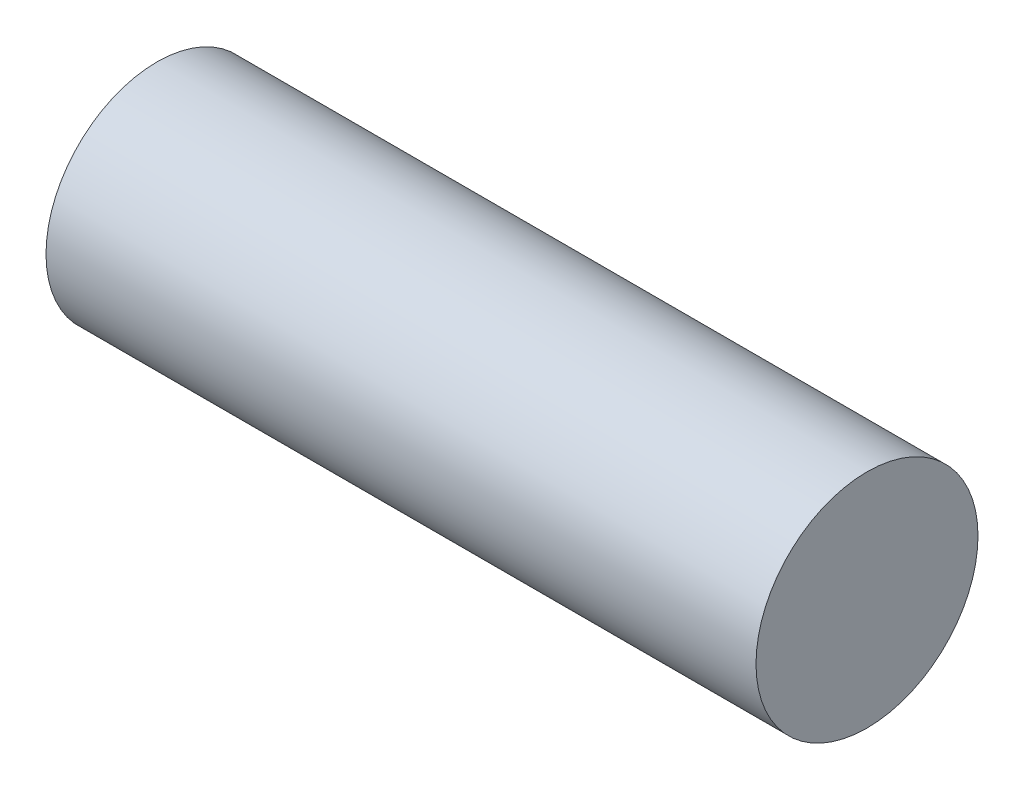
SolidWorks part; units mm, degrees
material "Chrome Stainless Steel"
ref_plane "Front Plane" through (0, 0, 0) normal (0, 0, 1) x (1, 0, 0)
ref_plane "Top Plane" through (0, 0, 0) normal (0, 1, 0) x (1, 0, 0)
ref_plane "Right Plane" through (0, 0, 0) normal (1, 0, 0) x (0, 0, -1)
sketch "Sketch2" plane through (0, 0, 0) normal (1, 0, 0) x (0, 0, -1)
  circle A0 centre (0, 0) radius 3
  dimension "D1" = 6
extrude "Boss-Extrude1" add sketch "Sketch2" along normal blind 19.19 contours A0
